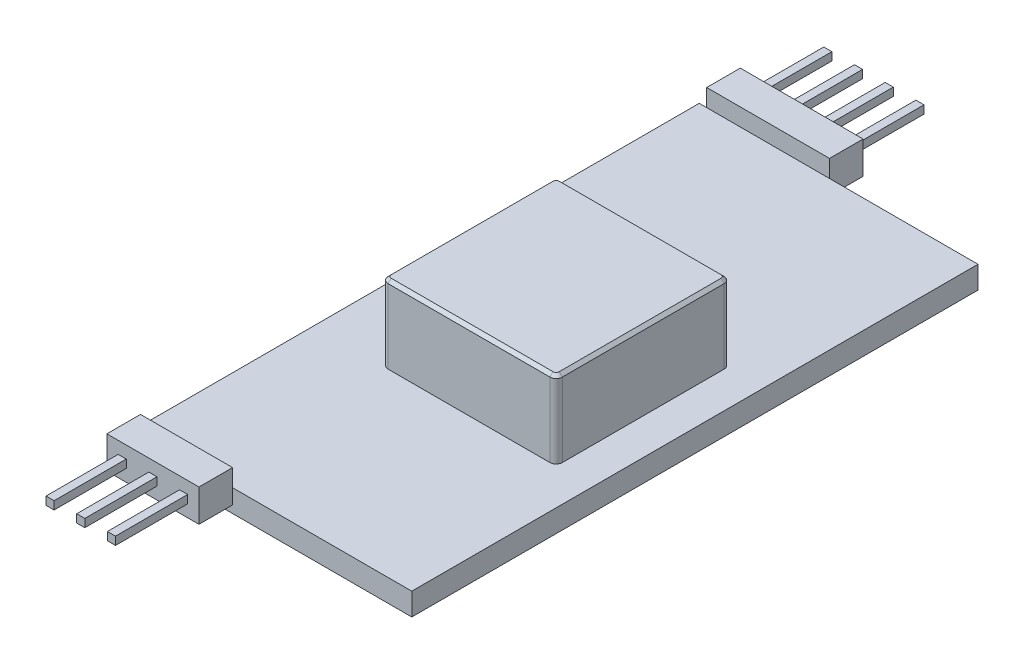
SolidWorks part; units mm, degrees
ref_plane "Front Plane" through (0, 0, 0) normal (0, 0, 1) x (1, 0, 0)
ref_plane "Top Plane" through (0, 0, 0) normal (0, 1, 0) x (1, 0, 0)
ref_plane "Right Plane" through (0, 0, 0) normal (1, 0, 0) x (0, 0, -1)
sketch "Sketch1" plane through (0, 0, 0) normal (0, 1, 0) x (1, 0, 0)
  line L1 (-11.2, -22.75) -> (11.2, -22.75)
  line L2 (-11.2, -22.75) -> (-11.2, 22.75)
  line L3 (-11.2, 22.75) -> (11.2, 22.75)
  line L4 (11.2, -22.75) -> (11.2, 22.75)
  line L5 (-11.2, -22.75) -> (11.2, 22.75) construction
  line L6 (-11.2, 22.75) -> (11.2, -22.75) construction
  point P0 (0, 0)
  dimension "D1" = 22.4
  dimension "D2" = 45.5
extrude "Boss-Extrude1" add sketch "Sketch1" along normal blind 1.8
sketch "Sketch2" plane through (0, 1.8, 0) normal (0, 1, 0) x (1, 0, 0)
  line L0 (11.2, 22.75) -> (-11.2, 22.75) construction
  line L1 (-5.7, 5.75) -> (8.3, 5.75)
  line L2 (-5.7, 5.75) -> (-5.7, -8.25)
  line L3 (-5.7, -8.25) -> (8.3, -8.25)
  line L4 (8.3, 5.75) -> (8.3, -8.25)
  line L5 (11.2, -22.75) -> (11.2, 22.75) construction
  dimension "D1" = 14
  dimension "D2" = 17
  dimension "D3" = 2.9
extrude "Boss-Extrude2" add sketch "Sketch2" along normal blind 8 from surface at -1.8 starting at face at (0, 0, 0)
sketch "Sketch3" plane through (0, 0, 22.75) normal (0, 0, 1) x (1, 0, 0)
  line L0 (-11.2, 1.8) -> (-11.2, 0) construction
  line L1 (-10.6, 0.6) -> (-3.2, 0.6)
  line L2 (-10.6, 0.6) -> (-10.6, 3.2)
  line L3 (-10.6, 3.2) -> (-3.2, 3.2)
  line L4 (-3.2, 0.6) -> (-3.2, 3.2)
  line L5 (-10.6, 0.6) -> (-3.2, 3.2) construction
  line L6 (-10.6, 3.2) -> (-3.2, 0.6) construction
  line L7 (-11.2, 0) -> (11.2, 0) construction
  point P0 (-6.9, 1.9)
  dimension "D1" = 0.6
  dimension "D2" = 0.6
  dimension "D3" = 7.4
  dimension "D4" = 2.6
extrude "Boss-Extrude3" add sketch "Sketch3" along normal blind 2.7
sketch "Sketch4" plane through (0, 0, 25.45) normal (0, 0, 1) x (1, 0, 0)
  line L0 (-10.6, 3.2) -> (-10.6, 0.6) construction
  line L1 (-9.6917, 1.575) -> (-9.0417, 1.575)
  line L2 (-9.6917, 1.575) -> (-9.6917, 2.225)
  line L3 (-9.6917, 2.225) -> (-9.0417, 2.225)
  line L4 (-9.0417, 1.575) -> (-9.0417, 2.225)
  line L5 (-9.6917, 1.575) -> (-9.0417, 2.225) construction
  line L6 (-9.6917, 2.225) -> (-9.0417, 1.575) construction
  line L7 (-7.225, 1.575) -> (-6.575, 1.575)
  line L8 (-7.225, 1.575) -> (-7.225, 2.225)
  line L9 (-7.225, 2.225) -> (-6.575, 2.225)
  line L10 (-6.575, 1.575) -> (-6.575, 2.225)
  line L11 (-7.225, 1.575) -> (-6.575, 2.225) construction
  line L12 (-7.225, 2.225) -> (-6.575, 1.575) construction
  line L13 (-4.7583, 1.575) -> (-4.1083, 1.575)
  line L14 (-4.7583, 1.575) -> (-4.7583, 2.225)
  line L15 (-4.7583, 2.225) -> (-4.1083, 2.225)
  line L16 (-4.1083, 1.575) -> (-4.1083, 2.225)
  line L17 (-4.7583, 1.575) -> (-4.1083, 2.225) construction
  line L18 (-4.7583, 2.225) -> (-4.1083, 1.575) construction
  line L19 (-10.6, 1.9) -> (-9.3667, 1.9) construction
  line L20 (-9.3667, 1.9) -> (-8.1333, 1.9) construction
  line L21 (-8.1333, 1.9) -> (-6.9, 1.9) construction
  line L22 (-6.9, 1.9) -> (-5.6667, 1.9) construction
  line L23 (-5.6667, 1.9) -> (-4.4333, 1.9) construction
  line L25 (-4.4333, 1.9) -> (-3.2, 1.9) construction
  line L26 (-3.2, 0.6) -> (-3.2, 3.2) construction
  point P0 (-9.3667, 1.9)
  point P5 (-6.9, 1.9)
  point P10 (-4.4333, 1.9)
  point P17 (-10.6, 1.9)
  dimension "D1" = 0.65
extrude "Boss-Extrude4" add sketch "Sketch4" along normal blind 5.8
sketch "Sketch6" plane through (0, 0, -22.75) normal (0, 0, -1) x (-1, 0, 0)
  line L0 (-11.2, 0) -> (11.2, 0) construction
  line L1 (0.733, 0.6) -> (10.6, 0.6)
  line L2 (0.733, 0.6) -> (0.733, 3.2)
  line L3 (0.733, 3.2) -> (10.6, 3.2)
  line L4 (10.6, 0.6) -> (10.6, 3.2)
  line L5 (0.733, 0.6) -> (10.6, 3.2) construction
  line L6 (0.733, 3.2) -> (10.6, 0.6) construction
  line L7 (11.2, 1.8) -> (11.2, 0) construction
  point P0 (5.6665, 1.9)
  dimension "D1" = 0.6
  dimension "D2" = 0.6
  dimension "D3" = 2.6
  dimension "D4" = 9.867
extrude "Boss-Extrude5" add sketch "Sketch6" along normal blind 2.7
sketch "Sketch7" plane through (0, 0, -25.45) normal (0, 0, -1) x (-1, 0, 0)
  line L0 (0.733, 3.2) -> (0.733, 0.6) construction
  line L1 (1.6414, 1.575) -> (2.2914, 1.575)
  line L2 (1.6414, 1.575) -> (1.6414, 2.225)
  line L3 (1.6414, 2.225) -> (2.2914, 2.225)
  line L4 (2.2914, 1.575) -> (2.2914, 2.225)
  line L5 (1.6414, 1.575) -> (2.2914, 2.225) construction
  line L6 (1.6414, 2.225) -> (2.2914, 1.575) construction
  line L7 (4.1081, 1.575) -> (4.7581, 1.575)
  line L8 (4.1081, 1.575) -> (4.1081, 2.225)
  line L9 (4.1081, 2.225) -> (4.7581, 2.225)
  line L10 (4.7581, 1.575) -> (4.7581, 2.225)
  line L11 (4.1081, 1.575) -> (4.7581, 2.225) construction
  line L12 (4.1081, 2.225) -> (4.7581, 1.575) construction
  line L13 (6.5749, 1.575) -> (7.2249, 1.575)
  line L14 (6.5749, 1.575) -> (6.5749, 2.225)
  line L15 (6.5749, 2.225) -> (7.2249, 2.225)
  line L16 (7.2249, 1.575) -> (7.2249, 2.225)
  line L17 (6.5749, 1.575) -> (7.2249, 2.225) construction
  line L18 (6.5749, 2.225) -> (7.2249, 1.575) construction
  line L19 (9.0416, 1.575) -> (9.6916, 1.575)
  line L20 (9.0416, 1.575) -> (9.0416, 2.225)
  line L21 (9.0416, 2.225) -> (9.6916, 2.225)
  line L22 (9.6916, 1.575) -> (9.6916, 2.225)
  line L23 (9.0416, 1.575) -> (9.6916, 2.225) construction
  line L24 (9.0416, 2.225) -> (9.6916, 1.575) construction
  line L25 (0.733, 1.9) -> (1.9664, 1.9) construction
  line L26 (1.9664, 1.9) -> (3.1997, 1.9) construction
  line L27 (3.1997, 1.9) -> (4.4331, 1.9) construction
  line L28 (4.4331, 1.9) -> (5.6665, 1.9) construction
  line L29 (5.6665, 1.9) -> (6.8999, 1.9) construction
  line L30 (6.8999, 1.9) -> (8.1332, 1.9) construction
  line L31 (8.1332, 1.9) -> (9.3666, 1.9) construction
  line L32 (9.3666, 1.9) -> (10.6, 1.9) construction
  line L34 (10.6, 0.6) -> (10.6, 3.2) construction
  point P0 (1.9664, 1.9)
  point P5 (4.4331, 1.9)
  point P10 (6.8999, 1.9)
  point P15 (9.3666, 1.9)
  point P23 (0.733, 1.9)
  dimension "D1" = 0.65
extrude "Boss-Extrude6" add sketch "Sketch7" along normal blind 5.8
fillet "Fillet1" radius 0.5 4 edges at (-5.7, 4.9, -5.75) (8.3, 4.9, -5.75) (8.3, 4.9, 8.25) (-5.7, 4.9, 8.25)
chamfer "Chamfer1" distance 0.25 angle 45 8 edges at (1.3, 8, -5.75) (8.1536, 8, -5.6036) (-5.5536, 8, -5.6036) (8.3, 8, 1.25) (-5.7, 8, 1.25) (8.1536, 8, 8.1036) (-5.5536, 8, 8.1036) (1.3, 8, 8.25)
